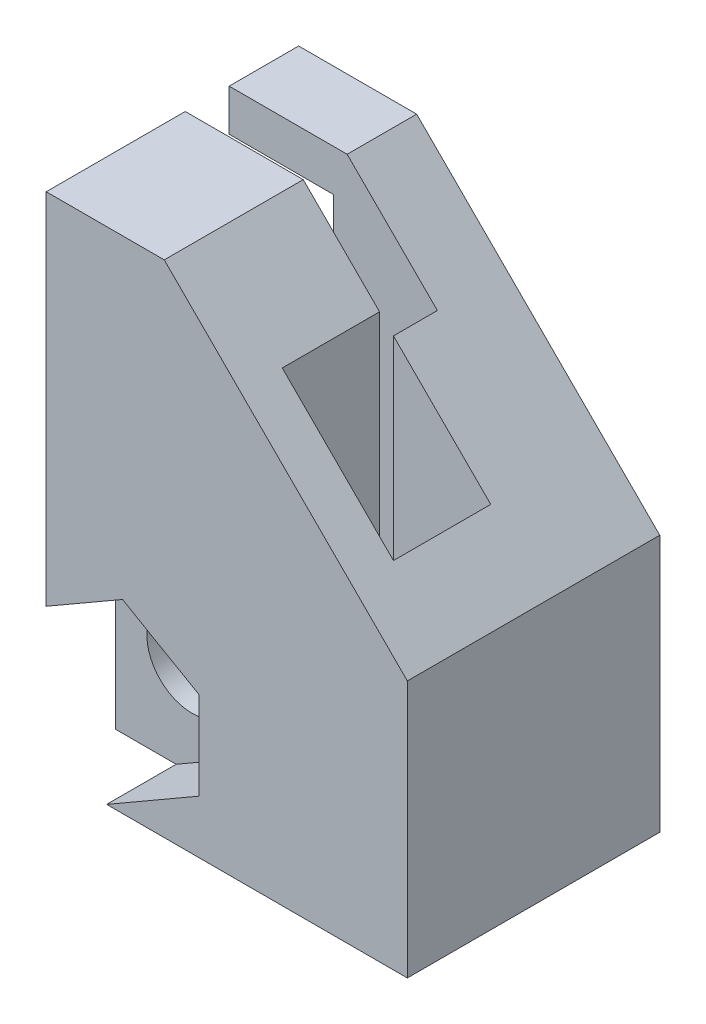
SolidWorks part; units mm, degrees
ref_plane "Alzado" through (0, 0, 0) normal (0, 0, 1) x (1, 0, 0)
ref_plane "Planta" through (0, 0, 0) normal (0, 1, 0) x (1, 0, 0)
ref_plane "Vista lateral" through (0, 0, 0) normal (1, 0, 0) x (0, 0, -1)
sketch "Croquis2" plane through (0, 0, -1.58) normal (0, 0, -1) x (-1, 0, 0)
  line L0 (-199.9998, -57.9999) -> (-197.9998, -55.9999)
  line L1 (-197.9998, -55.9999) -> (-193.7545, -55.9999)
  line L2 (-121.9998, -55.9999) -> (-197.9998, -55.9999) construction
  line L3 (-193.7545, -57.4999) -> (-197.5045, -57.4999)
  line L4 (-193.7545, -57.4999) -> (-193.7545, -55.9999)
  line L5 (-197.5045, -64.7452) -> (-192.4998, -64.7452)
  line L6 (-197.5045, -64.7452) -> (-197.5045, -57.4999)
  line L7 (-192.4998, -64.7452) -> (-192.4998, -73.9999)
  line L8 (-197.9998, -73.9999) -> (-121.9998, -73.9999) construction
  line L9 (-192.4998, -73.9999) -> (-206.7451, -73.9999)
  line L10 (-199.9998, -57.9999) -> (-206.7451, -64.7452)
  line L11 (-206.7451, -64.7452) -> (-206.7451, -73.9999)
  circle A0 centre (-196.4998, -70.4999) radius 1.625
  dimension "D1" = 3.25
  dimension "D2" = 178.4939
  dimension "D3" = 179.7486
  dimension "D4" = 183.4986
  dimension "D5" = 192.7392
  dimension "D6" = 207.7188
extrude "Saliente-Extruir1" add sketch "Croquis2" along normal blind 2.5
sketch "Croquis4" plane through (0, 0, -4.08) normal (0, 0, -1) x (-1, 0, 0)
  circle A1 centre (-196.4998, -70.4999) radius 3.36
  dimension "D1" = 6.7199
extrude "Cortar-Extruir1" cut sketch "Croquis4" against normal blind 1.8 draft 44
sketch "Croquis5" plane through (0, 0, -1.58) normal (0, 0, 1) x (1, 0, 0)
  line L0 (206.7451, -73.9999) -> (201.2451, -73.9999)
  line L1 (206.7451, -73.9999) -> (192.4998, -73.9999) construction
  line L2 (206.7451, -73.9999) -> (206.7451, -64.7452)
  line L3 (206.7451, -64.7452) -> (201.2451, -59.2452)
  line L4 (197.9998, -55.9999) -> (206.7451, -64.7452) construction
  line L5 (201.2451, -59.2452) -> (201.2451, -73.9999)
  line L6 (193.7545, -57.4999) -> (193.7545, -55.9999) construction
  dimension "D1" = 7.4906
extrude "Saliente-Extruir2" add sketch "Croquis5" along normal up to vertex (1.58 mm away)
sketch "Croquis6" plane through (0, 0, 0) normal (0, 0, 1) x (1, 0, 0)
  line L4 (193.7545, -55.9999) -> (193.7545, -73.9999)
  line L5 (201.2451, -73.9999) -> (192.4998, -73.9999) construction
  line L11 (206.7451, -73.9999) -> (204.7451, -73.9999)
  line L12 (201.2451, -73.9999) -> (206.7451, -73.9999) construction
  line L13 (204.7451, -73.9999) -> (204.7451, -62.7452)
  line L14 (206.7451, -64.7452) -> (201.2451, -59.2452) construction
  line L15 (204.7451, -62.7452) -> (206.7451, -64.7452)
  line L16 (206.7451, -64.7452) -> (206.7451, -73.9999)
  line L17 (206.7451, -73.9999) -> (206.7451, -64.7452) construction
  line L18 (193.7545, -55.9999) -> (197.9998, -55.9999)
  line L19 (197.9998, -55.9999) -> (200.7451, -58.7452)
  line L20 (197.9998, -55.9999) -> (201.2451, -59.2452) construction
  line L21 (200.7451, -58.7452) -> (200.7451, -73.9999)
  line L22 (200.7451, -73.9999) -> (193.7545, -73.9999)
  circle A0 centre (196.4998, -70.4999) radius 1.625
  dimension "D3" = 3.25
  dimension "D1" = 2
  dimension "D2" = 6
extrude "Saliente-Extruir3" add sketch "Croquis6" along normal blind 3.5
sketch "Croquis9" plane through (0, 0, 3.5) normal (0, 0, 1) x (1, 0, 0)
  line L1 (193.7545, -55.9999) -> (197.9998, -55.9999)
  line L2 (197.9998, -55.9999) -> (206.7451, -64.7452)
  line L3 (206.7451, -64.7452) -> (206.7451, -73.9999)
  line L4 (206.7451, -73.9999) -> (193.7545, -73.9999)
  line L10 (197.9998, -55.9999) -> (193.7545, -55.9999) construction
  line L11 (193.7545, -55.9999) -> (193.7545, -73.9999)
  circle A0 centre (196.4998, -70.4999) radius 1.625
  dimension "D1" = 3.25
extrude "Saliente-Extruir5" add sketch "Croquis9" along normal blind 1.5
sketch "Croquis10" plane through (0, 0, 5) normal (0, 0, 1) x (1, 0, 0)
  line L0 (193.7545, -55.9999) -> (193.7545, -73.9999) construction
  line L1 (196.4998, -67.3299) -> (193.7545, -68.9149)
  line L2 (193.7545, -68.9149) -> (193.7545, -70.4999)
  line L5 (199.2451, -72.0849) -> (199.2451, -68.9149)
  line L6 (199.2451, -68.9149) -> (196.4998, -67.3299)
  line L8 (195.1272, -72.8774) -> (196.4998, -73.6699) [skipped]
  line L9 (193.7545, -70.4999) -> (193.7545, -73.9999)
  line L10 (199.2451, -72.0849) -> (196.4998, -73.6699)
  line L11 (196.4998, -73.6699) -> (195.9283, -73.9999)
  line L12 (193.7545, -73.9999) -> (206.7451, -73.9999) construction
  line L13 (195.9283, -73.9999) -> (193.7545, -73.9999)
  line L15 (196.4998, -73.6699) -> (199.2451, -72.0849) [skipped]
  dimension "D1" = 1.3727
  dimension "D2" = 2.1737
  dimension "D3" = 2.7453
  dimension "D4" = 3.5
extrude "Cortar-Extruir2" cut sketch "Croquis10" against normal blind 2.5
